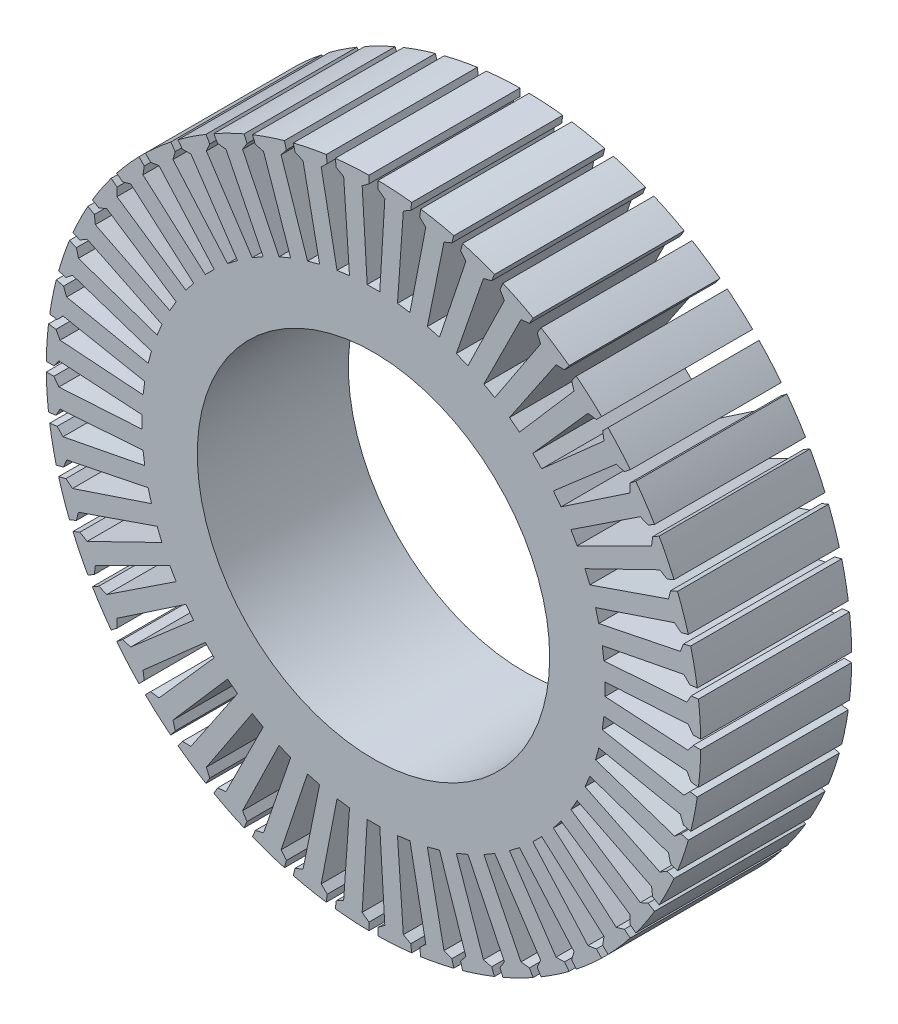
SolidWorks part; units mm, degrees
ref_plane "Спереди" through (0, 0, 0) normal (0, 0, 1) x (1, 0, 0)
ref_plane "Сверху" through (0, 0, 0) normal (0, 1, 0) x (1, 0, 0)
ref_plane "Справа" through (0, 0, 0) normal (1, 0, 0) x (0, 0, -1)
sketch "Эскиз1" plane through (0, 0, 0) normal (0, 0, 1) x (1, 0, 0)
  circle A0 centre (0, 0) radius 65
  circle A1 centre (0, 0) radius 35
extrude "Stator_stack" add sketch "Эскиз1" along normal blind 30 from offset 15
sketch "Эскиз2" plane through (0, 0, 0) normal (0, 0, 1) x (1, 0, 0)
  line L0 (65.9939, -0.9) -> (63.5, -0.9)
  line L1 (63.5, -0.9) -> (62.5, -2.25)
  line L2 (62.5, -2.25) -> (46, -1.25)
  line L3 (46, -1.25) -> (46, 1.25)
  line L4 (46, 1.25) -> (62.5, 2.25)
  line L5 (62.5, 2.25) -> (63.5, 0.9)
  line L6 (63.5, 0.9) -> (65.9939, 0.9)
  line L7 (65.9939, 0.9) -> (65.9939, -0.9)
  line L8 (65.5468, 7.7216) -> (63.0742, 7.3961)
  line L9 (63.0742, 7.3961) -> (62.259, 5.9271)
  line L10 (62.259, 5.9271) -> (45.7696, 4.7649)
  line L11 (45.7696, 4.7649) -> (45.4433, 7.2435)
  line L12 (45.4433, 7.2435) -> (61.6716, 10.3886)
  line L13 (61.6716, 10.3886) -> (62.8393, 9.1807)
  line L14 (62.8393, 9.1807) -> (65.3118, 9.5062)
  line L15 (65.3118, 9.5062) -> (65.5468, 7.7216)
  line L16 (63.9781, 16.2111) -> (61.5692, 15.5657)
  line L17 (61.5692, 15.5657) -> (60.9527, 14.0029)
  line L18 (60.9527, 14.0029) -> (44.7561, 10.6983)
  line L19 (44.7561, 10.6983) -> (44.1091, 13.1131)
  line L20 (44.1091, 13.1131) -> (59.788, 18.3495)
  line L21 (59.788, 18.3495) -> (61.1034, 17.3043)
  line L22 (61.1034, 17.3043) -> (63.5122, 17.9498)
  line L23 (63.5122, 17.9498) -> (63.9781, 16.2111)
  line L24 (61.3148, 24.4233) -> (59.0108, 23.4689)
  line L25 (59.0108, 23.4689) -> (58.6035, 21.839)
  line L26 (58.6035, 21.839) -> (42.9768, 16.4486)
  line L27 (42.9768, 16.4486) -> (42.0201, 18.7583)
  line L28 (42.0201, 18.7583) -> (56.8814, 25.9964)
  line L29 (56.8814, 25.9964) -> (58.3219, 25.1319)
  line L30 (58.3219, 25.1319) -> (60.626, 26.0862)
  line L31 (60.626, 26.0862) -> (61.3148, 24.4233)
  line L32 (57.6024, 32.2175) -> (55.4426, 30.9706)
  line L33 (55.4426, 30.9706) -> (55.2516, 29.3014)
  line L34 (55.2516, 29.3014) -> (40.4622, 21.9175)
  line L35 (40.4622, 21.9175) -> (39.2122, 24.0825)
  line L36 (39.2122, 24.0825) -> (53.0016, 33.1986)
  line L37 (53.0016, 33.1986) -> (54.5426, 32.5294)
  line L38 (54.5426, 32.5294) -> (56.7024, 33.7764)
  line L39 (56.7024, 33.7764) -> (57.6024, 32.2175)
  line L40 (52.9043, 39.4605) -> (50.9258, 37.9423)
  line L41 (50.9258, 37.9423) -> (50.9543, 36.2625)
  line L42 (50.9543, 36.2625) -> (37.2552, 27.0113)
  line L43 (37.2552, 27.0113) -> (35.7333, 28.9947)
  line L44 (35.7333, 28.9947) -> (48.2149, 39.8326)
  line L45 (48.2149, 39.8326) -> (49.8301, 39.3704)
  line L46 (49.8301, 39.3704) -> (51.8086, 40.8885)
  line L47 (51.8086, 40.8885) -> (52.9043, 39.4605)
  line L48 (47.3011, 46.0283) -> (45.5377, 44.2649)
  line L49 (45.5377, 44.2649) -> (45.7852, 42.6032)
  line L50 (45.7852, 42.6032) -> (33.4108, 31.643)
  line L51 (33.4108, 31.643) -> (31.643, 33.4108)
  line L52 (31.643, 33.4108) -> (42.6032, 45.7852)
  line L53 (42.6032, 45.7852) -> (44.2649, 45.5377)
  line L54 (44.2649, 45.5377) -> (46.0283, 47.3011)
  line L55 (46.0283, 47.3011) -> (47.3011, 46.0283)
  line L56 (40.8885, 51.8086) -> (39.3704, 49.8301)
  line L57 (39.3704, 49.8301) -> (39.8326, 48.2149)
  line L58 (39.8326, 48.2149) -> (28.9947, 35.7333)
  line L59 (28.9947, 35.7333) -> (27.0113, 37.2552)
  line L60 (27.0113, 37.2552) -> (36.2625, 50.9543)
  line L61 (36.2625, 50.9543) -> (37.9423, 50.9258)
  line L62 (37.9423, 50.9258) -> (39.4605, 52.9043)
  line L63 (39.4605, 52.9043) -> (40.8885, 51.8086)
  line L64 (33.7764, 56.7024) -> (32.5294, 54.5426)
  line L65 (32.5294, 54.5426) -> (33.1986, 53.0016)
  line L66 (33.1986, 53.0016) -> (24.0825, 39.2122)
  line L67 (24.0825, 39.2122) -> (21.9175, 40.4622)
  line L68 (21.9175, 40.4622) -> (29.3014, 55.2516)
  line L69 (29.3014, 55.2516) -> (30.9706, 55.4426)
  line L70 (30.9706, 55.4426) -> (32.2175, 57.6024)
  line L71 (32.2175, 57.6024) -> (33.7764, 56.7024)
  line L72 (26.0862, 60.626) -> (25.1319, 58.3219)
  line L73 (25.1319, 58.3219) -> (25.9964, 56.8814)
  line L74 (25.9964, 56.8814) -> (18.7583, 42.0201)
  line L75 (18.7583, 42.0201) -> (16.4486, 42.9768)
  line L76 (16.4486, 42.9768) -> (21.839, 58.6035)
  line L77 (21.839, 58.6035) -> (23.4689, 59.0108)
  line L78 (23.4689, 59.0108) -> (24.4233, 61.3148)
  line L79 (24.4233, 61.3148) -> (26.0862, 60.626)
  line L80 (17.9498, 63.5122) -> (17.3043, 61.1034)
  line L81 (17.3043, 61.1034) -> (18.3495, 59.788)
  line L82 (18.3495, 59.788) -> (13.1131, 44.1091)
  line L83 (13.1131, 44.1091) -> (10.6983, 44.7561)
  line L84 (10.6983, 44.7561) -> (14.0029, 60.9527)
  line L85 (14.0029, 60.9527) -> (15.5657, 61.5692)
  line L86 (15.5657, 61.5692) -> (16.2111, 63.9781)
  line L87 (16.2111, 63.9781) -> (17.9498, 63.5122)
  line L88 (9.5062, 65.3118) -> (9.1807, 62.8393)
  line L89 (9.1807, 62.8393) -> (10.3886, 61.6716)
  line L90 (10.3886, 61.6716) -> (7.2435, 45.4433)
  line L91 (7.2435, 45.4433) -> (4.7649, 45.7696)
  line L92 (4.7649, 45.7696) -> (5.9271, 62.259)
  line L93 (5.9271, 62.259) -> (7.3961, 63.0742)
  line L94 (7.3961, 63.0742) -> (7.7216, 65.5468)
  line L95 (7.7216, 65.5468) -> (9.5062, 65.3118)
  line L96 (0.9, 65.9939) -> (0.9, 63.5)
  line L97 (0.9, 63.5) -> (2.25, 62.5)
  line L98 (2.25, 62.5) -> (1.25, 46)
  line L99 (1.25, 46) -> (-1.25, 46)
  line L100 (-1.25, 46) -> (-2.25, 62.5)
  line L101 (-2.25, 62.5) -> (-0.9, 63.5)
  line L102 (-0.9, 63.5) -> (-0.9, 65.9939)
  line L103 (-0.9, 65.9939) -> (0.9, 65.9939)
  line L104 (-7.7216, 65.5468) -> (-7.3961, 63.0742)
  line L105 (-7.3961, 63.0742) -> (-5.9271, 62.259)
  line L106 (-5.9271, 62.259) -> (-4.7649, 45.7696)
  line L107 (-4.7649, 45.7696) -> (-7.2435, 45.4433)
  line L108 (-7.2435, 45.4433) -> (-10.3886, 61.6716)
  line L109 (-10.3886, 61.6716) -> (-9.1807, 62.8393)
  line L110 (-9.1807, 62.8393) -> (-9.5062, 65.3118)
  line L111 (-9.5062, 65.3118) -> (-7.7216, 65.5468)
  line L112 (-16.2111, 63.9781) -> (-15.5657, 61.5692)
  line L113 (-15.5657, 61.5692) -> (-14.0029, 60.9527)
  line L114 (-14.0029, 60.9527) -> (-10.6983, 44.7561)
  line L115 (-10.6983, 44.7561) -> (-13.1131, 44.1091)
  line L116 (-13.1131, 44.1091) -> (-18.3495, 59.788)
  line L117 (-18.3495, 59.788) -> (-17.3043, 61.1034)
  line L118 (-17.3043, 61.1034) -> (-17.9498, 63.5122)
  line L119 (-17.9498, 63.5122) -> (-16.2111, 63.9781)
  line L120 (-24.4233, 61.3148) -> (-23.4689, 59.0108)
  line L121 (-23.4689, 59.0108) -> (-21.839, 58.6035)
  line L122 (-21.839, 58.6035) -> (-16.4486, 42.9768)
  line L123 (-16.4486, 42.9768) -> (-18.7583, 42.0201)
  line L124 (-18.7583, 42.0201) -> (-25.9964, 56.8814)
  line L125 (-25.9964, 56.8814) -> (-25.1319, 58.3219)
  line L126 (-25.1319, 58.3219) -> (-26.0862, 60.626)
  line L127 (-26.0862, 60.626) -> (-24.4233, 61.3148)
  line L128 (-32.2175, 57.6024) -> (-30.9706, 55.4426)
  line L129 (-30.9706, 55.4426) -> (-29.3014, 55.2516)
  line L130 (-29.3014, 55.2516) -> (-21.9175, 40.4622)
  line L131 (-21.9175, 40.4622) -> (-24.0825, 39.2122)
  line L132 (-24.0825, 39.2122) -> (-33.1986, 53.0016)
  line L133 (-33.1986, 53.0016) -> (-32.5294, 54.5426)
  line L134 (-32.5294, 54.5426) -> (-33.7764, 56.7024)
  line L135 (-33.7764, 56.7024) -> (-32.2175, 57.6024)
  line L136 (-39.4605, 52.9043) -> (-37.9423, 50.9258)
  line L137 (-37.9423, 50.9258) -> (-36.2625, 50.9543)
  line L138 (-36.2625, 50.9543) -> (-27.0113, 37.2552)
  line L139 (-27.0113, 37.2552) -> (-28.9947, 35.7333)
  line L140 (-28.9947, 35.7333) -> (-39.8326, 48.2149)
  line L141 (-39.8326, 48.2149) -> (-39.3704, 49.8301)
  line L142 (-39.3704, 49.8301) -> (-40.8885, 51.8086)
  line L143 (-40.8885, 51.8086) -> (-39.4605, 52.9043)
  line L144 (-46.0283, 47.3011) -> (-44.2649, 45.5377)
  line L145 (-44.2649, 45.5377) -> (-42.6032, 45.7852)
  line L146 (-42.6032, 45.7852) -> (-31.643, 33.4108)
  line L147 (-31.643, 33.4108) -> (-33.4108, 31.643)
  line L148 (-33.4108, 31.643) -> (-45.7852, 42.6032)
  line L149 (-45.7852, 42.6032) -> (-45.5377, 44.2649)
  line L150 (-45.5377, 44.2649) -> (-47.3011, 46.0283)
  line L151 (-47.3011, 46.0283) -> (-46.0283, 47.3011)
  line L152 (-51.8086, 40.8885) -> (-49.8301, 39.3704)
  line L153 (-49.8301, 39.3704) -> (-48.2149, 39.8326)
  line L154 (-48.2149, 39.8326) -> (-35.7333, 28.9947)
  line L155 (-35.7333, 28.9947) -> (-37.2552, 27.0113)
  line L156 (-37.2552, 27.0113) -> (-50.9543, 36.2625)
  line L157 (-50.9543, 36.2625) -> (-50.9258, 37.9423)
  line L158 (-50.9258, 37.9423) -> (-52.9043, 39.4605)
  line L159 (-52.9043, 39.4605) -> (-51.8086, 40.8885)
  line L160 (-56.7024, 33.7764) -> (-54.5426, 32.5294)
  line L161 (-54.5426, 32.5294) -> (-53.0016, 33.1986)
  line L162 (-53.0016, 33.1986) -> (-39.2122, 24.0825)
  line L163 (-39.2122, 24.0825) -> (-40.4622, 21.9175)
  line L164 (-40.4622, 21.9175) -> (-55.2516, 29.3014)
  line L165 (-55.2516, 29.3014) -> (-55.4426, 30.9706)
  line L166 (-55.4426, 30.9706) -> (-57.6024, 32.2175)
  line L167 (-57.6024, 32.2175) -> (-56.7024, 33.7764)
  line L168 (-60.626, 26.0862) -> (-58.3219, 25.1319)
  line L169 (-58.3219, 25.1319) -> (-56.8814, 25.9964)
  line L170 (-56.8814, 25.9964) -> (-42.0201, 18.7583)
  line L171 (-42.0201, 18.7583) -> (-42.9768, 16.4486)
  line L172 (-42.9768, 16.4486) -> (-58.6035, 21.839)
  line L173 (-58.6035, 21.839) -> (-59.0108, 23.4689)
  line L174 (-59.0108, 23.4689) -> (-61.3148, 24.4233)
  line L175 (-61.3148, 24.4233) -> (-60.626, 26.0862)
  line L176 (-63.5122, 17.9498) -> (-61.1034, 17.3043)
  line L177 (-61.1034, 17.3043) -> (-59.788, 18.3495)
  line L178 (-59.788, 18.3495) -> (-44.1091, 13.1131)
  line L179 (-44.1091, 13.1131) -> (-44.7561, 10.6983)
  line L180 (-44.7561, 10.6983) -> (-60.9527, 14.0029)
  line L181 (-60.9527, 14.0029) -> (-61.5692, 15.5657)
  line L182 (-61.5692, 15.5657) -> (-63.9781, 16.2111)
  line L183 (-63.9781, 16.2111) -> (-63.5122, 17.9498)
  line L184 (-65.3118, 9.5062) -> (-62.8393, 9.1807)
  line L185 (-62.8393, 9.1807) -> (-61.6716, 10.3886)
  line L186 (-61.6716, 10.3886) -> (-45.4433, 7.2435)
  line L187 (-45.4433, 7.2435) -> (-45.7696, 4.7649)
  line L188 (-45.7696, 4.7649) -> (-62.259, 5.9271)
  line L189 (-62.259, 5.9271) -> (-63.0742, 7.3961)
  line L190 (-63.0742, 7.3961) -> (-65.5468, 7.7216)
  line L191 (-65.5468, 7.7216) -> (-65.3118, 9.5062)
  line L192 (-65.9939, 0.9) -> (-63.5, 0.9)
  line L193 (-63.5, 0.9) -> (-62.5, 2.25)
  line L194 (-62.5, 2.25) -> (-46, 1.25)
  line L195 (-46, 1.25) -> (-46, -1.25)
  line L196 (-46, -1.25) -> (-62.5, -2.25)
  line L197 (-62.5, -2.25) -> (-63.5, -0.9)
  line L198 (-63.5, -0.9) -> (-65.9939, -0.9)
  line L199 (-65.9939, -0.9) -> (-65.9939, 0.9)
  line L200 (-65.5468, -7.7216) -> (-63.0742, -7.3961)
  line L201 (-63.0742, -7.3961) -> (-62.259, -5.9271)
  line L202 (-62.259, -5.9271) -> (-45.7696, -4.7649)
  line L203 (-45.7696, -4.7649) -> (-45.4433, -7.2435)
  line L204 (-45.4433, -7.2435) -> (-61.6716, -10.3886)
  line L205 (-61.6716, -10.3886) -> (-62.8393, -9.1807)
  line L206 (-62.8393, -9.1807) -> (-65.3118, -9.5062)
  line L207 (-65.3118, -9.5062) -> (-65.5468, -7.7216)
  line L208 (-63.9781, -16.2111) -> (-61.5692, -15.5657)
  line L209 (-61.5692, -15.5657) -> (-60.9527, -14.0029)
  line L210 (-60.9527, -14.0029) -> (-44.7561, -10.6983)
  line L211 (-44.7561, -10.6983) -> (-44.1091, -13.1131)
  line L212 (-44.1091, -13.1131) -> (-59.788, -18.3495)
  line L213 (-59.788, -18.3495) -> (-61.1034, -17.3043)
  line L214 (-61.1034, -17.3043) -> (-63.5122, -17.9498)
  line L215 (-63.5122, -17.9498) -> (-63.9781, -16.2111)
  line L216 (-61.3148, -24.4233) -> (-59.0108, -23.4689)
  line L217 (-59.0108, -23.4689) -> (-58.6035, -21.839)
  line L218 (-58.6035, -21.839) -> (-42.9768, -16.4486)
  line L219 (-42.9768, -16.4486) -> (-42.0201, -18.7583)
  line L220 (-42.0201, -18.7583) -> (-56.8814, -25.9964)
  line L221 (-56.8814, -25.9964) -> (-58.3219, -25.1319)
  line L222 (-58.3219, -25.1319) -> (-60.626, -26.0862)
  line L223 (-60.626, -26.0862) -> (-61.3148, -24.4233)
  line L224 (-57.6024, -32.2175) -> (-55.4426, -30.9706)
  line L225 (-55.4426, -30.9706) -> (-55.2516, -29.3014)
  line L226 (-55.2516, -29.3014) -> (-40.4622, -21.9175)
  line L227 (-40.4622, -21.9175) -> (-39.2122, -24.0825)
  line L228 (-39.2122, -24.0825) -> (-53.0016, -33.1986)
  line L229 (-53.0016, -33.1986) -> (-54.5426, -32.5294)
  line L230 (-54.5426, -32.5294) -> (-56.7024, -33.7764)
  line L231 (-56.7024, -33.7764) -> (-57.6024, -32.2175)
  line L232 (-52.9043, -39.4605) -> (-50.9258, -37.9423)
  line L233 (-50.9258, -37.9423) -> (-50.9543, -36.2625)
  line L234 (-50.9543, -36.2625) -> (-37.2552, -27.0113)
  line L235 (-37.2552, -27.0113) -> (-35.7333, -28.9947)
  line L236 (-35.7333, -28.9947) -> (-48.2149, -39.8326)
  line L237 (-48.2149, -39.8326) -> (-49.8301, -39.3704)
  line L238 (-49.8301, -39.3704) -> (-51.8086, -40.8885)
  line L239 (-51.8086, -40.8885) -> (-52.9043, -39.4605)
  line L240 (-47.3011, -46.0283) -> (-45.5377, -44.2649)
  line L241 (-45.5377, -44.2649) -> (-45.7852, -42.6032)
  line L242 (-45.7852, -42.6032) -> (-33.4108, -31.643)
  line L243 (-33.4108, -31.643) -> (-31.643, -33.4108)
  line L244 (-31.643, -33.4108) -> (-42.6032, -45.7852)
  line L245 (-42.6032, -45.7852) -> (-44.2649, -45.5377)
  line L246 (-44.2649, -45.5377) -> (-46.0283, -47.3011)
  line L247 (-46.0283, -47.3011) -> (-47.3011, -46.0283)
  line L248 (-40.8885, -51.8086) -> (-39.3704, -49.8301)
  line L249 (-39.3704, -49.8301) -> (-39.8326, -48.2149)
  line L250 (-39.8326, -48.2149) -> (-28.9947, -35.7333)
  line L251 (-28.9947, -35.7333) -> (-27.0113, -37.2552)
  line L252 (-27.0113, -37.2552) -> (-36.2625, -50.9543)
  line L253 (-36.2625, -50.9543) -> (-37.9423, -50.9258)
  line L254 (-37.9423, -50.9258) -> (-39.4605, -52.9043)
  line L255 (-39.4605, -52.9043) -> (-40.8885, -51.8086)
  line L256 (-33.7764, -56.7024) -> (-32.5294, -54.5426)
  line L257 (-32.5294, -54.5426) -> (-33.1986, -53.0016)
  line L258 (-33.1986, -53.0016) -> (-24.0825, -39.2122)
  line L259 (-24.0825, -39.2122) -> (-21.9175, -40.4622)
  line L260 (-21.9175, -40.4622) -> (-29.3014, -55.2516)
  line L261 (-29.3014, -55.2516) -> (-30.9706, -55.4426)
  line L262 (-30.9706, -55.4426) -> (-32.2175, -57.6024)
  line L263 (-32.2175, -57.6024) -> (-33.7764, -56.7024)
  line L264 (-26.0862, -60.626) -> (-25.1319, -58.3219)
  line L265 (-25.1319, -58.3219) -> (-25.9964, -56.8814)
  line L266 (-25.9964, -56.8814) -> (-18.7583, -42.0201)
  line L267 (-18.7583, -42.0201) -> (-16.4486, -42.9768)
  line L268 (-16.4486, -42.9768) -> (-21.839, -58.6035)
  line L269 (-21.839, -58.6035) -> (-23.4689, -59.0108)
  line L270 (-23.4689, -59.0108) -> (-24.4233, -61.3148)
  line L271 (-24.4233, -61.3148) -> (-26.0862, -60.626)
  line L272 (-17.9498, -63.5122) -> (-17.3043, -61.1034)
  line L273 (-17.3043, -61.1034) -> (-18.3495, -59.788)
  line L274 (-18.3495, -59.788) -> (-13.1131, -44.1091)
  line L275 (-13.1131, -44.1091) -> (-10.6983, -44.7561)
  line L276 (-10.6983, -44.7561) -> (-14.0029, -60.9527)
  line L277 (-14.0029, -60.9527) -> (-15.5657, -61.5692)
  line L278 (-15.5657, -61.5692) -> (-16.2111, -63.9781)
  line L279 (-16.2111, -63.9781) -> (-17.9498, -63.5122)
  line L280 (-9.5062, -65.3118) -> (-9.1807, -62.8393)
  line L281 (-9.1807, -62.8393) -> (-10.3886, -61.6716)
  line L282 (-10.3886, -61.6716) -> (-7.2435, -45.4433)
  line L283 (-7.2435, -45.4433) -> (-4.7649, -45.7696)
  line L284 (-4.7649, -45.7696) -> (-5.9271, -62.259)
  line L285 (-5.9271, -62.259) -> (-7.3961, -63.0742)
  line L286 (-7.3961, -63.0742) -> (-7.7216, -65.5468)
  line L287 (-7.7216, -65.5468) -> (-9.5062, -65.3118)
  line L288 (-0.9, -65.9939) -> (-0.9, -63.5)
  line L289 (-0.9, -63.5) -> (-2.25, -62.5)
  line L290 (-2.25, -62.5) -> (-1.25, -46)
  line L291 (-1.25, -46) -> (1.25, -46)
  line L292 (1.25, -46) -> (2.25, -62.5)
  line L293 (2.25, -62.5) -> (0.9, -63.5)
  line L294 (0.9, -63.5) -> (0.9, -65.9939)
  line L295 (0.9, -65.9939) -> (-0.9, -65.9939)
  line L296 (7.7216, -65.5468) -> (7.3961, -63.0742)
  line L297 (7.3961, -63.0742) -> (5.9271, -62.259)
  line L298 (5.9271, -62.259) -> (4.7649, -45.7696)
  line L299 (4.7649, -45.7696) -> (7.2435, -45.4433)
  line L300 (7.2435, -45.4433) -> (10.3886, -61.6716)
  line L301 (10.3886, -61.6716) -> (9.1807, -62.8393)
  line L302 (9.1807, -62.8393) -> (9.5062, -65.3118)
  line L303 (9.5062, -65.3118) -> (7.7216, -65.5468)
  line L304 (16.2111, -63.9781) -> (15.5657, -61.5692)
  line L305 (15.5657, -61.5692) -> (14.0029, -60.9527)
  line L306 (14.0029, -60.9527) -> (10.6983, -44.7561)
  line L307 (10.6983, -44.7561) -> (13.1131, -44.1091)
  line L308 (13.1131, -44.1091) -> (18.3495, -59.788)
  line L309 (18.3495, -59.788) -> (17.3043, -61.1034)
  line L310 (17.3043, -61.1034) -> (17.9498, -63.5122)
  line L311 (17.9498, -63.5122) -> (16.2111, -63.9781)
  line L312 (24.4233, -61.3148) -> (23.4689, -59.0108)
  line L313 (23.4689, -59.0108) -> (21.839, -58.6035)
  line L314 (21.839, -58.6035) -> (16.4486, -42.9768)
  line L315 (16.4486, -42.9768) -> (18.7583, -42.0201)
  line L316 (18.7583, -42.0201) -> (25.9964, -56.8814)
  line L317 (25.9964, -56.8814) -> (25.1319, -58.3219)
  line L318 (25.1319, -58.3219) -> (26.0862, -60.626)
  line L319 (26.0862, -60.626) -> (24.4233, -61.3148)
  line L320 (32.2175, -57.6024) -> (30.9706, -55.4426)
  line L321 (30.9706, -55.4426) -> (29.3014, -55.2516)
  line L322 (29.3014, -55.2516) -> (21.9175, -40.4622)
  line L323 (21.9175, -40.4622) -> (24.0825, -39.2122)
  line L324 (24.0825, -39.2122) -> (33.1986, -53.0016)
  line L325 (33.1986, -53.0016) -> (32.5294, -54.5426)
  line L326 (32.5294, -54.5426) -> (33.7764, -56.7024)
  line L327 (33.7764, -56.7024) -> (32.2175, -57.6024)
  line L328 (39.4605, -52.9043) -> (37.9423, -50.9258)
  line L329 (37.9423, -50.9258) -> (36.2625, -50.9543)
  line L330 (36.2625, -50.9543) -> (27.0113, -37.2552)
  line L331 (27.0113, -37.2552) -> (28.9947, -35.7333)
  line L332 (28.9947, -35.7333) -> (39.8326, -48.2149)
  line L333 (39.8326, -48.2149) -> (39.3704, -49.8301)
  line L334 (39.3704, -49.8301) -> (40.8885, -51.8086)
  line L335 (40.8885, -51.8086) -> (39.4605, -52.9043)
  line L336 (46.0283, -47.3011) -> (44.2649, -45.5377)
  line L337 (44.2649, -45.5377) -> (42.6032, -45.7852)
  line L338 (42.6032, -45.7852) -> (31.643, -33.4108)
  line L339 (31.643, -33.4108) -> (33.4108, -31.643)
  line L340 (33.4108, -31.643) -> (45.7852, -42.6032)
  line L341 (45.7852, -42.6032) -> (45.5377, -44.2649)
  line L342 (45.5377, -44.2649) -> (47.3011, -46.0283)
  line L343 (47.3011, -46.0283) -> (46.0283, -47.3011)
  line L344 (51.8086, -40.8885) -> (49.8301, -39.3704)
  line L345 (49.8301, -39.3704) -> (48.2149, -39.8326)
  line L346 (48.2149, -39.8326) -> (35.7333, -28.9947)
  line L347 (35.7333, -28.9947) -> (37.2552, -27.0113)
  line L348 (37.2552, -27.0113) -> (50.9543, -36.2625)
  line L349 (50.9543, -36.2625) -> (50.9258, -37.9423)
  line L350 (50.9258, -37.9423) -> (52.9043, -39.4605)
  line L351 (52.9043, -39.4605) -> (51.8086, -40.8885)
  line L352 (56.7024, -33.7764) -> (54.5426, -32.5294)
  line L353 (54.5426, -32.5294) -> (53.0016, -33.1986)
  line L354 (53.0016, -33.1986) -> (39.2122, -24.0825)
  line L355 (39.2122, -24.0825) -> (40.4622, -21.9175)
  line L356 (40.4622, -21.9175) -> (55.2516, -29.3014)
  line L357 (55.2516, -29.3014) -> (55.4426, -30.9706)
  line L358 (55.4426, -30.9706) -> (57.6024, -32.2175)
  line L359 (57.6024, -32.2175) -> (56.7024, -33.7764)
  line L360 (60.626, -26.0862) -> (58.3219, -25.1319)
  line L361 (58.3219, -25.1319) -> (56.8814, -25.9964)
  line L362 (56.8814, -25.9964) -> (42.0201, -18.7583)
  line L363 (42.0201, -18.7583) -> (42.9768, -16.4486)
  line L364 (42.9768, -16.4486) -> (58.6035, -21.839)
  line L365 (58.6035, -21.839) -> (59.0108, -23.4689)
  line L366 (59.0108, -23.4689) -> (61.3148, -24.4233)
  line L367 (61.3148, -24.4233) -> (60.626, -26.0862)
  line L368 (63.5122, -17.9498) -> (61.1034, -17.3043)
  line L369 (61.1034, -17.3043) -> (59.788, -18.3495)
  line L370 (59.788, -18.3495) -> (44.1091, -13.1131)
  line L371 (44.1091, -13.1131) -> (44.7561, -10.6983)
  line L372 (44.7561, -10.6983) -> (60.9527, -14.0029)
  line L373 (60.9527, -14.0029) -> (61.5692, -15.5657)
  line L374 (61.5692, -15.5657) -> (63.9781, -16.2111)
  line L375 (63.9781, -16.2111) -> (63.5122, -17.9498)
  line L376 (65.3118, -9.5062) -> (62.8393, -9.1807)
  line L377 (62.8393, -9.1807) -> (61.6716, -10.3886)
  line L378 (61.6716, -10.3886) -> (45.4433, -7.2435)
  line L379 (45.4433, -7.2435) -> (45.7696, -4.7649)
  line L380 (45.7696, -4.7649) -> (62.259, -5.9271)
  line L381 (62.259, -5.9271) -> (63.0742, -7.3961)
  line L382 (63.0742, -7.3961) -> (65.5468, -7.7216)
  line L383 (65.5468, -7.7216) -> (65.3118, -9.5062)
extrude "Stator_48_slots" cut sketch "Эскиз2" against normal mid plane 32
